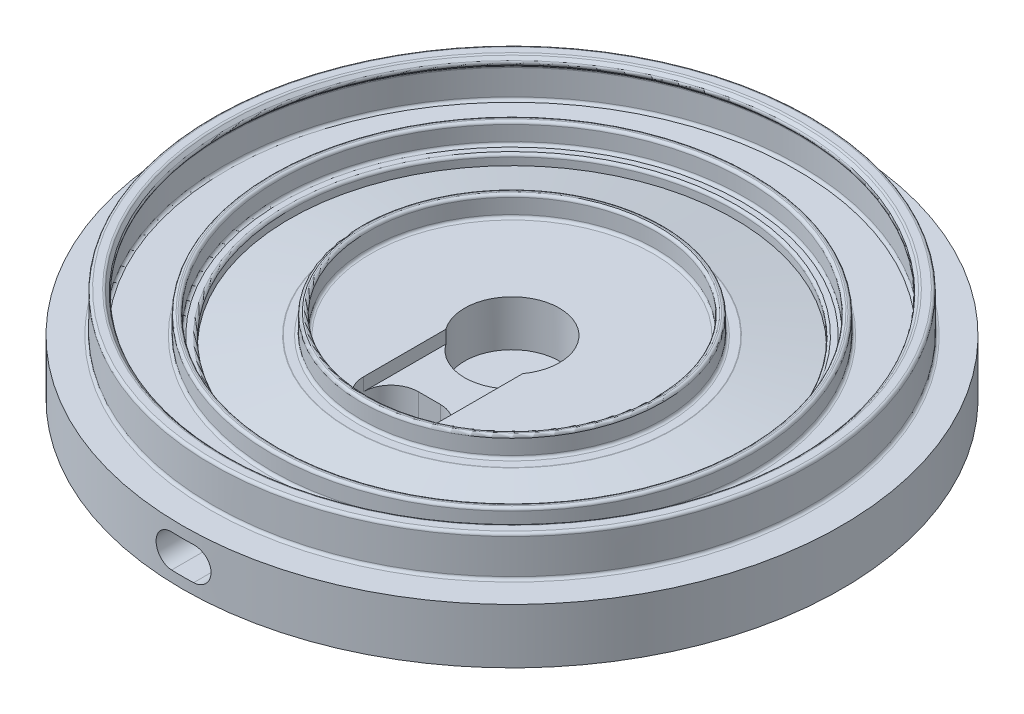
SolidWorks part; units mm, degrees
ref_plane "Front Plane" through (0, 0, 0) normal (0, 0, 1) x (1, 0, 0)
ref_plane "Top Plane" through (0, 0, 0) normal (0, 1, 0) x (1, 0, 0)
ref_plane "Right Plane" through (0, 0, 0) normal (1, 0, 0) x (0, 0, -1)
sketch "Sketch1" plane through (0, 0, 0) normal (0, 1, 0) x (1, 0, 0)
  circle A0 centre (0, 0) radius 60
  circle A1 centre (0, 0) radius 40
  circle A2 centre (0, 0) radius 30
  dimension "D1" = 60
  dimension "D2" = 80
  dimension "D3" = 120
extrude "Boss-Extrude1" add sketch "Sketch1" along normal blind 10 contours A0
sketch "Sketch2" plane through (0, 0, 0) normal (0, 0, 1) x (1, 0, 0)
  line L0 (0, 10) -> (-29.5, 10)
  line L1 (60, 10) -> (-60, 10) construction
  line L2 (-29.5, 10) -> (-40.5, 8.127)
  line L3 (-40.5, 8.127) -> (-40.5, 10)
  line L4 (-40.5, 10) -> (-29.5, 10)
  line L5 (0, 10) -> (0, 0) construction
  dimension "D1" = 11
  dimension "D2" = 29.5
  dimension "D3" = 1.873
revolve "Cut-Revolve1" cut sketch "Sketch2" angle 360 about L5
sketch "Sketch3" plane through (0, 10, 0) normal (0, 1, 0) x (1, 0, 0)
  circle A0 centre (0, 0) radius 27.5
  circle A1 centre (0, 0) radius 26.25
  circle A2 centre (0, 0) radius 42.5
  circle A3 centre (0, 0) radius 43.75
  dimension "D1" = 55
  dimension "D2" = 52.5
  dimension "D3" = 85
  dimension "D4" = 87.5
extrude "Boss-Extrude2" add sketch "Sketch3" along normal blind 3.723 contours A1 | A0 | A2 | A3
fillet "Fillet1" radius 0.5 10 edges at (0, 10, 26.25) (0, 10, 27.5) (0, 10, 43.75) (0, 10, 42.5) (0, 10, 40.5) (0, 13.723, 27.5) (0, 13.723, 26.25) (0, 13.723, 43.75) (0, 13.723, 42.5) (0, 10, 29.5)
sketch "Sketch5" plane through (0, 0, 0) normal (0, 0, 1) x (1, 0, 0)
  line L0 (0, 10) -> (-52.5, 10) construction
  line L1 (60, 10) -> (-60, 10) construction
  line L2 (-52.5, 10) -> (-54.5, 10)
  line L3 (-54.5, 10) -> (-54.5, 17.323)
  line L4 (-54.5, 17.323) -> (-52.5, 17.323)
  line L5 (-52.5, 17.323) -> (-51.5, 16.323)
  line L6 (-51.5, 16.323) -> (-52.5, 15.323)
  line L7 (-52.5, 15.323) -> (-52.5, 10)
  line L8 (0, 10) -> (0, 24.5479) construction
  line L9 (0, -7.5476) -> (0, 7.5476) construction
  dimension "D1" = 52.5
  dimension "D2" = 7.323
  dimension "D3" = 1
  dimension "D4" = 1
  dimension "D5" = 2
  dimension "D6" = 2
revolve "Revolve1" add sketch "Sketch5" angle 360 about L8
fillet "Fillet2" radius 0.5 6 edges at (0, 10, -52.5) (0, 15.323, -52.5) (0, 17.323, -52.5) (0, 16.323, -51.5) (0, 10, -54.5) (0, 17.323, -54.5)
sketch "Sketch6" plane through (0, 10, 0) normal (0, 1, 0) x (1, 0, 0)
  circle A0 centre (0, 0) radius 8.625
  dimension "D1" = 17.25
extrude "Cut-Extrude1" cut sketch "Sketch6" against normal blind 8.354
sketch "Sketch9" plane through (0, 10, 0) normal (0, 1, 0) x (1, 0, 0)
  line L1 (-7, -5.0389) -> (7, -5.0389)
  line L2 (-7, -5.0389) -> (-7, -20.0389)
  line L3 (-7, -20.0389) -> (7, -20.0389)
  line L4 (7, -5.0389) -> (7, -20.0389)
  circle A0 centre (0, 0) radius 8.625 construction
  circle A1 centre (0, 0) radius 8.625 construction
  dimension "D1" = 15
  dimension "D2" = 14
extrude "Cut-Extrude2" cut sketch "Sketch9" against normal blind 2.354
sketch "Sketch10" plane through (0, 10, 0) normal (0, 1, 0) x (1, 0, 0)
  line L0 (2, -20.0389) -> (-2, -20.0389) construction
  line L1 (-7, -20.0389) -> (7, -20.0389) construction
  line L2 (2, -25.0389) -> (-2, -25.0389)
  line L3 (2, -15.0389) -> (-2, -15.0389)
  arc A0 (2, -25.0389) -> (2, -15.0389) centre (2, -20.0389) ccw
  arc A1 (-2, -15.0389) -> (-2, -25.0389) centre (-2, -20.0389) ccw
  point P4 (0, -20.0389)
  dimension "D1" = 5
extrude "Cut-Extrude3" cut sketch "Sketch10" against normal blind 10
sketch "Sketch11" plane through (0, 0, 25.0389) normal (0, 0, -1) x (-1, 0, 0)
  line L0 (-2, 5) -> (2, 5) construction
  line L1 (-2, 8) -> (2, 8)
  line L2 (-2, 2) -> (2, 2)
  line L3 (2, 0) -> (2, 10) construction
  line L4 (-2, 0) -> (-2, 10) construction
  line L5 (2, 0) -> (-2, 0) construction
  arc A0 (-2, 8) -> (-2, 2) centre (-2, 5) ccw
  arc A1 (2, 2) -> (2, 8) centre (2, 5) ccw
  point P2 (0, 5)
  point P7 (0, 0)
  point P10 (0, 0)
  dimension "D1" = 3
  dimension "D2" = 2
extrude "Cut-Extrude4" cut sketch "Sketch11" against normal blind 40 and the other way blind 2
